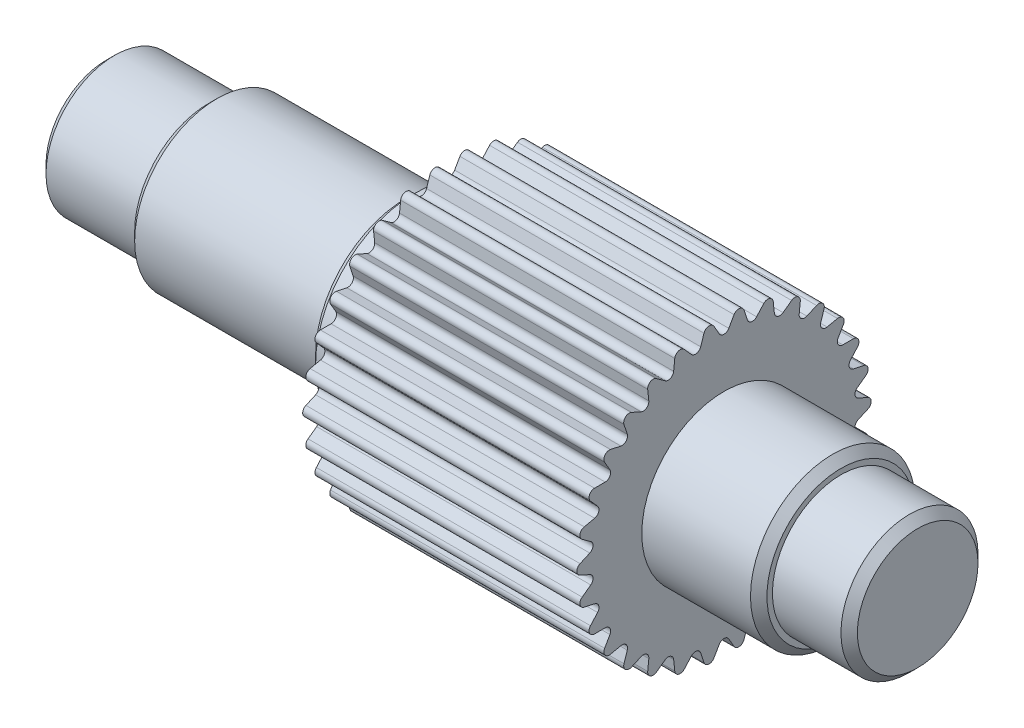
SolidWorks part; units mm, degrees
ref_plane "Спереди" through (0, 0, 0) normal (0, 0, 1) x (1, 0, 0)
ref_plane "Сверху" through (0, 0, 0) normal (0, 1, 0) x (1, 0, 0)
ref_plane "Справа" through (0, 0, 0) normal (1, 0, 0) x (0, 0, -1)
sketch "Эскиз1" plane through (0, 0, 0) normal (0, 0, 1) x (1, 0, 0)
  line L0 (0, 0) -> (97.87, 0) construction
  line L1 (0, 0) -> (0, -12.5)
  line L2 (0, -12.5) -> (18.6706, -12.5)
  line L3 (18.6706, -12.5) -> (18.6706, -15)
  line L6 (62.6706, -28.8) -> (112.6706, -28.8)
  line L7 (112.6706, -28.8) -> (112.6706, -15)
  line L8 (112.6706, -15) -> (134, -15)
  line L9 (134, -15) -> (134, -12.5)
  line L10 (134, -12.5) -> (148, -12.5)
  line L11 (148, -12.5) -> (148, 0)
  line L12 (148, 0) -> (0, 0)
  line L13 (18.6706, -15) -> (54.6706, -15)
  line L14 (54.6706, -15) -> (54.6706, -18)
  line L15 (54.6706, -18) -> (62.6706, -18)
  line L16 (62.6706, -18) -> (62.6706, -28.8)
  dimension "D1" = 148
  dimension "D2" = 50
  dimension "D3" = 14
  dimension "D4" = 18.6706
  dimension "D5" = 36
  dimension "D6" = 8
  dimension "D7" = 25
  dimension "D8" = 30
  dimension "D9" = 36
  dimension "D10" = 57.6
  dimension "D11" = 30
  dimension "D12" = 25
revolve "Повернуть1" add sketch "Эскиз1" angle 360 about L0
sketch "Эскиз2" plane through (0, 0, 0) normal (0, 0, 1) x (1, 0, 0)
  line L0 (0, 0) -> (148, 0) construction
  line L1 (148, -12.5) -> (148, 12.5) construction
  line L2 (0, 0) -> (0, 4.25)
  line L3 (0, 4.25) -> (3.9, 2)
  line L4 (3.9, 2) -> (8.9, 2)
  line L5 (8.9, 2) -> (10.0547, 0)
  line L6 (0, 0) -> (10.0547, 0)
  dimension "D1" = 60
  dimension "D2" = 5
  dimension "D3" = 8.5
  dimension "D4" = 4
  dimension "D5" = 3.9
revolve "Вырез-Повернуть1" cut sketch "Эскиз2" angle 360 about L0
ref_plane "Плоскость4" through (0, 0, -15) normal (0, 0, -1) x (-1, 0, 0)
sketch "Эскиз3" plane through (0, 0, -15) normal (0, 0, -1) x (-1, 0, 0)
  line L0 (-18.6706, 0) -> (-54.6706, 0) construction
  line L1 (-29.6706, 0) -> (-43.6706, 0) construction
  line L2 (-29.6706, -4) -> (-43.6706, -4)
  line L3 (-18.6706, -15) -> (-18.6706, 15) construction
  line L4 (-54.6706, -15) -> (-54.6706, 15) construction
  line L5 (-29.6706, 4) -> (-43.6706, 4)
  arc A0 (-29.6706, -4) -> (-29.6706, 4) centre (-29.6706, 0) ccw
  arc A1 (-43.6706, 4) -> (-43.6706, -4) centre (-43.6706, 0) ccw
  point P8 (-36.6706, 0)
  point P10 (-36.6706, 0)
  point P15 (-25.6706, 0)
  point P16 (-47.6706, 0)
  dimension "D1" = 22
  dimension "D2" = 8
extrude "Вырез-Вытянуть1" cut sketch "Эскиз3" along normal through all from offset 10 offset against normal yes
sketch "Эскиз4" plane through (112.6706, 0, 0) normal (1, 0, 0) x (0, 0, -1)
  line L1 (5, 31.6868) -> (-5, 31.6868)
  line L2 (-5, 31.6868) -> (0, 23.0265)
  line L3 (0, 23.0265) -> (5, 31.6868)
  circle A0 centre (0, 28.8) radius 2.8868 construction
  circle A1 centre (0, 0) radius 28.8 construction
  point P7 (8.7128, 27.4505)
  point P9 (0, 0)
  point P11 (0, 28.8)
  point P12 (1.8436, 34.5026)
  point P13 (-3.8802, 31.9063)
  point P14 (0, 28.8)
  point P15 (0, 0)
  dimension "D1" = 10
extrude "Вырез-Вытянуть3" cut sketch "Эскиз4" against normal up to next
pattern_circular "Круговой массив4" count 30 over 360 about axis through (0, 0, 0) along (1, 0, 0) of "Вырез-Вытянуть3"
fillet "Скругление4" radius 1 60 edges at (87.6706, 22.5233, -4.7875) (87.6706, 26.921, -8.7472) (87.6706, 21.0358, -9.3657) (87.6706, 24.5141, -14.1532) (87.6706, 18.6288, -13.5346) (87.6706, 21.0358, -18.9407) (87.6706, 15.4077, -17.112) (87.6706, 16.6381, -22.9004) (87.6706, 11.5132, -19.9415) (87.6706, 11.5132, -25.8592) (87.6706, 7.1156, -21.8995) (87.6706, 5.8852, -27.6878) (87.6706, 2.4069, -22.9004) (87.6706, -2.4069, -22.9004) (87.6706, -5.8852, -27.6878) (87.6706, -7.1156, -21.8995) (87.6706, -11.5132, -25.8592) (87.6706, -11.5132, -19.9415) (87.6706, -16.6381, -22.9004) (87.6706, -15.4077, -17.112) (87.6706, -21.0358, -18.9407) (87.6706, -18.6288, -13.5346) (87.6706, -24.5141, -14.1532) (87.6706, -21.0358, -9.3657) (87.6706, -26.921, -8.7472) (87.6706, -22.5233, -4.7875) (87.6706, -28.1513, -2.9588) (87.6706, -23.0265, 0) (87.6706, -28.1513, 2.9588) (87.6706, -22.5233, 4.7875) (87.6706, -26.921, 8.7472) (87.6706, -21.0358, 9.3657) (87.6706, -24.5141, 14.1532) (87.6706, -18.6288, 13.5346) (87.6706, -21.0358, 18.9407) (87.6706, -15.4077, 17.112) (87.6706, -16.6381, 22.9004) (87.6706, -11.5132, 19.9415) (87.6706, -11.5132, 25.8592) (87.6706, -7.1156, 21.8995) (87.6706, -5.8852, 27.6878) (87.6706, -2.4069, 22.9004) (87.6706, 0, 28.3064) (87.6706, 2.4069, 22.9004) (87.6706, 5.8852, 27.6878) (87.6706, 7.1156, 21.8995) (87.6706, 11.5132, 25.8592) (87.6706, 11.5132, 19.9415) (87.6706, 16.6381, 22.9004) (87.6706, 15.4077, 17.112) (87.6706, 21.0358, 18.9407) (87.6706, 18.6288, 13.5346) (87.6706, 24.5141, 14.1532) (87.6706, 21.0358, 9.3657) (87.6706, 26.921, 8.7472) (87.6706, 22.5233, 4.7875) (87.6706, 28.1513, 2.9588) (87.6706, 23.0265, 0) (87.6706, 28.1513, -2.9588) (87.6706, 0, -28.3064)
chamfer "Фаска1" distance 1.5 angle 45 5 edges at (54.6706, 0, 18) (18.6706, 0, 15) (0, 0, 12.5) (148, 0, 12.5) (134, 0, 15)
